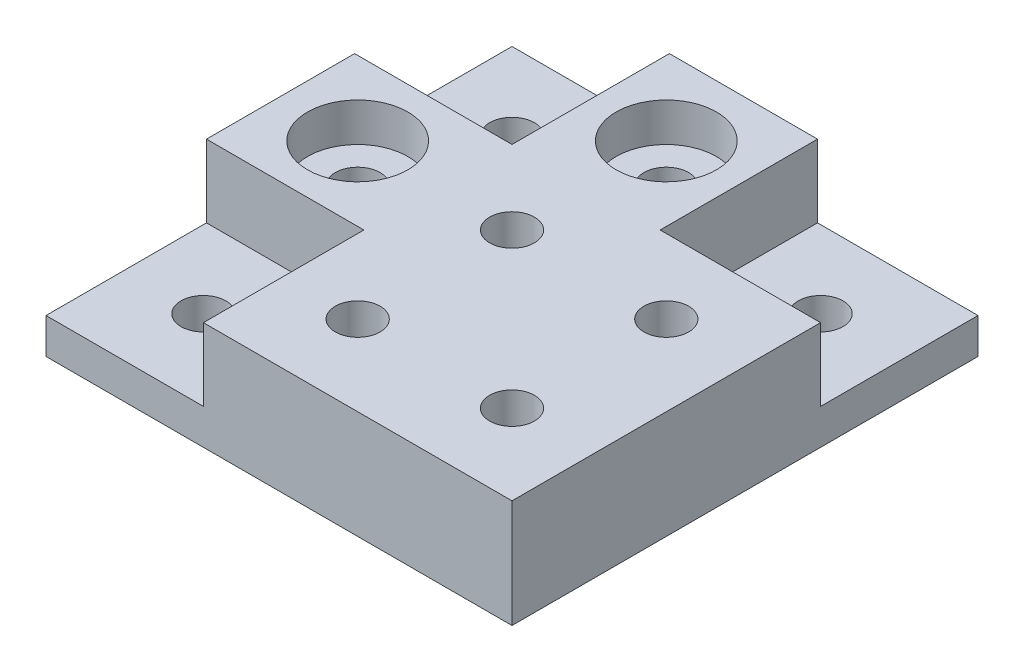
SolidWorks part; units mm, degrees
ref_plane "Alzado" through (0, 0, 0) normal (0, 0, 1) x (1, 0, 0)
ref_plane "Planta" through (0, 0, 0) normal (0, 1, 0) x (1, 0, 0)
ref_plane "Vista lateral" through (0, 0, 0) normal (1, 0, 0) x (0, 0, -1)
sketch "Croquis1" plane through (0, 0, 0) normal (0, 1, 0) x (1, 0, 0)
  line L1 (-50, -50) -> (50, -50)
  line L2 (-50, -50) -> (-50, 50)
  line L3 (-50, 50) -> (50, 50)
  line L4 (50, -50) -> (50, 50)
  line L5 (-50, -50) -> (50, 50) construction
  line L6 (-50, 50) -> (50, -50) construction
  point P0 (0, 0)
  dimension "D1" = 100
  dimension "D2" = 100
extrude "Saliente-Extruir1" add sketch "Croquis1" along normal blind 7
sketch "Croquis2" plane through (0, 7, 0) normal (0, 1, 0) x (1, 0, 0)
  line L45 (-50, 50) -> (-50, -50) construction
  line L50 (-50.2, 50.2) -> (-39.8, 50.2)
  line L55 (-50.2, 50.2) -> (-50.2, 39.8)
  line L60 (-50.2, 39.8) -> (-39.8, 39.8)
  line L65 (-39.8, 50.2) -> (-39.8, 39.8)
  line L70 (50, 50) -> (-50, 50) construction
  line L75 (-30.2, 50.2) -> (-19.8, 50.2)
  line L80 (-30.2, 50.2) -> (-30.2, 39.8)
  line L85 (-30.2, 39.8) -> (-19.8, 39.8)
  line L95 (-19.8, 50.2) -> (-19.8, 39.8)
  line L96 (-10.2, 50.2) -> (0.2, 50.2)
  line L97 (-10.2, 50.2) -> (-10.2, 39.8)
  line L98 (-10.2, 39.8) -> (0.2, 39.8)
  line L99 (0.2, 50.2) -> (0.2, 39.8)
  line L100 (9.8, 50.2) -> (20.2, 50.2)
  line L101 (9.8, 50.2) -> (9.8, 39.8)
  line L102 (9.8, 39.8) -> (20.2, 39.8)
  line L103 (20.2, 50.2) -> (20.2, 39.8)
  line L104 (29.8, 50.2) -> (40.2, 50.2)
  line L105 (29.8, 50.2) -> (29.8, 39.8)
  line L106 (29.8, 39.8) -> (40.2, 39.8)
  line L107 (40.2, 50.2) -> (40.2, 39.8)
  line L108 (-50.2, 30.2) -> (-39.8, 30.2)
  line L109 (-50.2, 30.2) -> (-50.2, 19.8)
  line L110 (-50.2, 19.8) -> (-39.8, 19.8)
  line L111 (-39.8, 30.2) -> (-39.8, 19.8)
  line L112 (-50.2, 10.2) -> (-39.8, 10.2)
  line L113 (-50.2, 10.2) -> (-50.2, -0.2)
  line L114 (-50.2, -0.2) -> (-39.8, -0.2)
  line L115 (-39.8, 10.2) -> (-39.8, -0.2)
  line L116 (-50.2, -9.8) -> (-39.8, -9.8)
  line L117 (-50.2, -9.8) -> (-50.2, -20.2)
  line L118 (-50.2, -20.2) -> (-39.8, -20.2)
  line L119 (-39.8, -9.8) -> (-39.8, -20.2)
  line L120 (-50.2, -29.8) -> (-39.8, -29.8)
  line L121 (-50.2, -29.8) -> (-50.2, -40.2)
  line L122 (-50.2, -40.2) -> (-39.8, -40.2)
  line L123 (-39.8, -29.8) -> (-39.8, -40.2)
  dimension "D3" = 0.2
  dimension "D1" = 10.4
  dimension "D2" = 10.4
  dimension "D4" = 0.2
  dimension "D5" = 5
extrude "Cortar-Extruir1" cut sketch "Croquis2" against normal blind 4.7
sketch "Croquis3" plane through (0, 7, 0) normal (0, 1, 0) x (1, 0, 0)
  line L0 (50, 30) -> (60, 30)
  line L5 (50, 50) -> (60, 50)
  line L6 (50, 50) -> (50, 40)
  line L7 (50, 40) -> (60, 40)
  line L8 (60, 50) -> (60, 40)
  line L9 (50, 30) -> (50, 20)
  line L10 (50, 20) -> (60, 20)
  line L11 (60, 30) -> (60, 20)
  line L12 (50, 10) -> (60, 10)
  line L13 (50, 10) -> (50, 0)
  line L14 (50, 0) -> (60, 0)
  line L15 (60, 10) -> (60, 0)
  line L16 (50, -10) -> (60, -10)
  line L17 (50, -10) -> (50, -20)
  line L18 (50, -20) -> (60, -20)
  line L19 (60, -10) -> (60, -20)
  line L20 (50, -30) -> (60, -30)
  line L21 (50, -30) -> (50, -40)
  line L22 (50, -40) -> (60, -40)
  line L23 (60, -30) -> (60, -40)
  line L24 (-30, -50) -> (-20, -50)
  line L25 (-50, -50) -> (-40, -50)
  line L26 (-50, -50) -> (-50, -60)
  line L27 (-50, -60) -> (-40, -60)
  line L28 (-40, -50) -> (-40, -60)
  line L29 (-30, -50) -> (-30, -60)
  line L30 (-30, -60) -> (-20, -60)
  line L31 (-20, -50) -> (-20, -60)
  line L32 (-10, -50) -> (0, -50)
  line L33 (-10, -50) -> (-10, -60)
  line L34 (-10, -60) -> (0, -60)
  line L35 (0, -50) -> (0, -60)
  line L36 (10, -50) -> (20, -50)
  line L37 (10, -50) -> (10, -60)
  line L38 (10, -60) -> (20, -60)
  line L39 (20, -50) -> (20, -60)
  line L40 (30, -50) -> (40, -50)
  line L41 (30, -50) -> (30, -60)
  line L42 (30, -60) -> (40, -60)
  line L43 (40, -50) -> (40, -60)
  dimension "D1" = 10
  dimension "D2" = 10
  dimension "D4" = 10
  dimension "D5" = 10
  dimension "D3" = 5
extrude "Saliente-Extruir2" add sketch "Croquis3" against normal blind 4.5
sketch "Croquis4" plane through (0, 7, 0) normal (0, 1, 0) x (1, 0, 0)
  line L0 (60, 45) -> (-63.1643, 45) construction
  line L1 (60, 40) -> (60, 50) construction
  line L2 (-45, -60) -> (-45, 61.9533) construction
  line L3 (-50, -60) -> (-40, -60) construction
  circle A0 centre (-45, 45) radius 1.45
  circle A1 centre (-35, 45) radius 1.45
  circle A2 centre (-25, 45) radius 1.45
  circle A3 centre (-15, 45) radius 1.45
  circle A4 centre (-5, 45) radius 1.45
  circle A5 centre (5, 45) radius 1.45
  circle A6 centre (15, 45) radius 1.45
  circle A7 centre (25, 45) radius 1.45
  circle A8 centre (35, 45) radius 1.45
  circle A9 centre (45, 45) radius 1.45
  circle A10 centre (55, 45) radius 1.45
  circle A11 centre (-35, 35) radius 1.45
  circle A12 centre (-25, 35) radius 1.45
  circle A13 centre (-15, 35) radius 1.45
  circle A14 centre (-5, 35) radius 1.45
  circle A15 centre (5, 35) radius 1.45
  circle A16 centre (15, 35) radius 1.45
  circle A17 centre (25, 35) radius 1.45
  circle A18 centre (35, 35) radius 1.45
  circle A19 centre (45, 35) radius 1.45
  circle A20 centre (55, 35) radius 1.45
  circle A21 centre (-35, 25) radius 1.45
  circle A22 centre (-25, 25) radius 1.45
  circle A23 centre (-15, 25) radius 1.45
  circle A24 centre (-5, 25) radius 1.45
  circle A25 centre (5, 25) radius 1.45
  circle A26 centre (15, 25) radius 1.45
  circle A27 centre (25, 25) radius 1.45
  circle A28 centre (35, 25) radius 1.45
  circle A29 centre (45, 25) radius 1.45
  circle A30 centre (55, 25) radius 1.45
  circle A31 centre (-35, 15) radius 1.45
  circle A32 centre (-25, 15) radius 1.45
  circle A33 centre (-15, 15) radius 1.45
  circle A34 centre (-5, 15) radius 1.45
  circle A35 centre (5, 15) radius 1.45
  circle A36 centre (15, 15) radius 1.45
  circle A37 centre (25, 15) radius 1.45
  circle A38 centre (35, 15) radius 1.45
  circle A39 centre (45, 15) radius 1.45
  circle A40 centre (55, 15) radius 1.45
  circle A41 centre (-35, 5) radius 1.45
  circle A42 centre (-25, 5) radius 1.45
  circle A43 centre (-15, 5) radius 1.45
  circle A44 centre (-5, 5) radius 1.45
  circle A45 centre (5, 5) radius 1.45
  circle A46 centre (15, 5) radius 1.45
  circle A47 centre (25, 5) radius 1.45
  circle A48 centre (35, 5) radius 1.45
  circle A49 centre (45, 5) radius 1.45
  circle A50 centre (55, 5) radius 1.45
  circle A51 centre (-35, -5) radius 1.45
  circle A52 centre (-25, -5) radius 1.45
  circle A53 centre (-15, -5) radius 1.45
  circle A54 centre (-5, -5) radius 1.45
  circle A55 centre (5, -5) radius 1.45
  circle A56 centre (15, -5) radius 1.45
  circle A57 centre (25, -5) radius 1.45
  circle A58 centre (35, -5) radius 1.45
  circle A59 centre (45, -5) radius 1.45
  circle A60 centre (55, -5) radius 1.45
  circle A61 centre (-35, -15) radius 1.45
  circle A62 centre (-25, -15) radius 1.45
  circle A63 centre (-15, -15) radius 1.45
  circle A64 centre (-5, -15) radius 1.45
  circle A65 centre (5, -15) radius 1.45
  circle A66 centre (15, -15) radius 1.45
  circle A67 centre (25, -15) radius 1.45
  circle A68 centre (35, -15) radius 1.45
  circle A69 centre (45, -15) radius 1.45
  circle A70 centre (55, -15) radius 1.45
  circle A71 centre (-35, -25) radius 1.45
  circle A72 centre (-25, -25) radius 1.45
  circle A73 centre (-15, -25) radius 1.45
  circle A74 centre (-5, -25) radius 1.45
  circle A75 centre (5, -25) radius 1.45
  circle A76 centre (15, -25) radius 1.45
  circle A77 centre (25, -25) radius 1.45
  circle A78 centre (35, -25) radius 1.45
  circle A79 centre (45, -25) radius 1.45
  circle A80 centre (55, -25) radius 1.45
  circle A81 centre (-35, -35) radius 1.45
  circle A82 centre (-25, -35) radius 1.45
  circle A83 centre (-15, -35) radius 1.45
  circle A84 centre (-5, -35) radius 1.45
  circle A85 centre (5, -35) radius 1.45
  circle A86 centre (15, -35) radius 1.45
  circle A87 centre (25, -35) radius 1.45
  circle A88 centre (35, -35) radius 1.45
  circle A89 centre (45, -35) radius 1.45
  circle A90 centre (55, -35) radius 1.45
  circle A91 centre (-35, -45) radius 1.45
  circle A92 centre (-25, -45) radius 1.45
  circle A93 centre (-15, -45) radius 1.45
  circle A94 centre (-5, -45) radius 1.45
  circle A95 centre (5, -45) radius 1.45
  circle A96 centre (15, -45) radius 1.45
  circle A97 centre (25, -45) radius 1.45
  circle A98 centre (35, -45) radius 1.45
  circle A99 centre (45, -45) radius 1.45
  circle A100 centre (55, -45) radius 1.45
  circle A101 centre (-35, -55) radius 1.45
  circle A102 centre (-25, -55) radius 1.45
  circle A103 centre (-15, -55) radius 1.45
  circle A104 centre (-5, -55) radius 1.45
  circle A105 centre (5, -55) radius 1.45
  circle A106 centre (15, -55) radius 1.45
  circle A107 centre (25, -55) radius 1.45
  circle A108 centre (35, -55) radius 1.45
  circle A109 centre (45, -55) radius 1.45
  circle A110 centre (55, -55) radius 1.45
  circle A111 centre (-45, 35) radius 1.45
  circle A112 centre (-45, 25) radius 1.45
  circle A113 centre (-45, 15) radius 1.45
  circle A114 centre (-45, 5) radius 1.45
  circle A115 centre (-45, -5) radius 1.45
  circle A116 centre (-45, -15) radius 1.45
  circle A117 centre (-45, -25) radius 1.45
  circle A118 centre (-45, -35) radius 1.45
  circle A119 centre (-45, -45) radius 1.45
  circle A120 centre (-45, -55) radius 1.45
  dimension "D1" = 2.9
  dimension "D2" = 11
extrude "Cortar-Extruir2" cut sketch "Croquis4" against normal blind 7
sketch "Croquis5" plane through (0, 7, 0) normal (0, 1, 0) x (1, 0, 0)
  circle A0 centre (-45, 45) radius 3.25
  circle A1 centre (-35, 45) radius 3.25
  circle A2 centre (-25, 45) radius 3.25
  circle A3 centre (-15, 45) radius 3.25
  circle A4 centre (-5, 45) radius 3.25
  circle A5 centre (5, 45) radius 3.25
  circle A6 centre (15, 45) radius 3.25
  circle A7 centre (25, 45) radius 3.25
  circle A8 centre (35, 45) radius 3.25
  circle A9 centre (45, 45) radius 3.25
  circle A10 centre (55, 45) radius 3.25
  circle A20 centre (55, 35) radius 3.25
  circle A30 centre (55, 25) radius 3.25
  circle A40 centre (55, 15) radius 3.25
  circle A50 centre (55, 5) radius 3.25
  circle A60 centre (55, -5) radius 3.25
  circle A70 centre (55, -15) radius 3.25
  circle A80 centre (55, -25) radius 3.25
  circle A90 centre (55, -35) radius 3.25
  circle A100 centre (55, -45) radius 3.25
  circle A101 centre (-35, -55) radius 3.25
  circle A102 centre (-25, -55) radius 3.25
  circle A103 centre (-15, -55) radius 3.25
  circle A104 centre (-5, -55) radius 3.25
  circle A105 centre (5, -55) radius 3.25
  circle A106 centre (15, -55) radius 3.25
  circle A107 centre (25, -55) radius 3.25
  circle A108 centre (35, -55) radius 3.25
  circle A109 centre (45, -55) radius 3.25
  circle A110 centre (55, -55) radius 3.25
  circle A111 centre (-45, 35) radius 3.25
  circle A112 centre (-45, 25) radius 3.25
  circle A113 centre (-45, 15) radius 3.25
  circle A114 centre (-45, 5) radius 3.25
  circle A115 centre (-45, -5) radius 3.25
  circle A116 centre (-45, -15) radius 3.25
  circle A117 centre (-45, -25) radius 3.25
  circle A118 centre (-45, -35) radius 3.25
  circle A119 centre (-45, -45) radius 3.25
  circle A120 centre (-45, -55) radius 3.25
  circle A121 centre (-35, 35) radius 3.25 [skipped]
  circle A122 centre (-25, 35) radius 3.25 [skipped]
  circle A123 centre (-15, 35) radius 3.25 [skipped]
  circle A124 centre (-5, 35) radius 3.25 [skipped]
  circle A125 centre (5, 35) radius 3.25 [skipped]
  circle A126 centre (15, 35) radius 3.25 [skipped]
  circle A127 centre (25, 35) radius 3.25 [skipped]
  circle A128 centre (35, 35) radius 3.25 [skipped]
  circle A129 centre (45, 35) radius 3.25 [skipped]
  circle A130 centre (-35, 25) radius 3.25 [skipped]
  circle A131 centre (-25, 25) radius 3.25 [skipped]
  circle A132 centre (-15, 25) radius 3.25 [skipped]
  circle A133 centre (-5, 25) radius 3.25 [skipped]
  circle A134 centre (5, 25) radius 3.25 [skipped]
  circle A135 centre (15, 25) radius 3.25 [skipped]
  circle A136 centre (25, 25) radius 3.25 [skipped]
  circle A137 centre (35, 25) radius 3.25 [skipped]
  circle A138 centre (45, 25) radius 3.25 [skipped]
  circle A139 centre (-35, 15) radius 3.25 [skipped]
  circle A140 centre (-25, 15) radius 3.25 [skipped]
  circle A141 centre (-15, 15) radius 3.25 [skipped]
  circle A142 centre (-5, 15) radius 3.25 [skipped]
  circle A143 centre (5, 15) radius 3.25 [skipped]
  circle A144 centre (15, 15) radius 3.25 [skipped]
  circle A145 centre (25, 15) radius 3.25 [skipped]
  circle A146 centre (35, 15) radius 3.25 [skipped]
  circle A147 centre (45, 15) radius 3.25 [skipped]
  circle A148 centre (-35, 5) radius 3.25 [skipped]
  circle A149 centre (-25, 5) radius 3.25 [skipped]
  circle A150 centre (-15, 5) radius 3.25 [skipped]
  circle A151 centre (-5, 5) radius 3.25 [skipped]
  circle A152 centre (5, 5) radius 3.25 [skipped]
  circle A153 centre (15, 5) radius 3.25 [skipped]
  circle A154 centre (25, 5) radius 3.25 [skipped]
  circle A155 centre (35, 5) radius 3.25 [skipped]
  circle A156 centre (45, 5) radius 3.25 [skipped]
  circle A157 centre (-35, -5) radius 3.25 [skipped]
  circle A158 centre (-25, -5) radius 3.25 [skipped]
  circle A159 centre (-15, -5) radius 3.25 [skipped]
  circle A160 centre (-5, -5) radius 3.25 [skipped]
  circle A161 centre (5, -5) radius 3.25 [skipped]
  circle A162 centre (15, -5) radius 3.25 [skipped]
  circle A163 centre (25, -5) radius 3.25 [skipped]
  circle A164 centre (35, -5) radius 3.25 [skipped]
  circle A165 centre (45, -5) radius 3.25 [skipped]
  circle A166 centre (-35, -15) radius 3.25 [skipped]
  circle A167 centre (-25, -15) radius 3.25 [skipped]
  circle A168 centre (-15, -15) radius 3.25 [skipped]
  circle A169 centre (-5, -15) radius 3.25 [skipped]
  circle A170 centre (5, -15) radius 3.25 [skipped]
  circle A171 centre (15, -15) radius 3.25 [skipped]
  circle A172 centre (25, -15) radius 3.25 [skipped]
  circle A173 centre (35, -15) radius 3.25 [skipped]
  circle A174 centre (45, -15) radius 3.25 [skipped]
  circle A175 centre (-35, -25) radius 3.25 [skipped]
  circle A176 centre (-25, -25) radius 3.25 [skipped]
  circle A177 centre (-15, -25) radius 3.25 [skipped]
  circle A178 centre (-5, -25) radius 3.25 [skipped]
  circle A179 centre (5, -25) radius 3.25 [skipped]
  circle A180 centre (15, -25) radius 3.25 [skipped]
  circle A181 centre (25, -25) radius 3.25 [skipped]
  circle A182 centre (35, -25) radius 3.25 [skipped]
  circle A183 centre (45, -25) radius 3.25 [skipped]
  circle A184 centre (-35, -35) radius 3.25 [skipped]
  circle A185 centre (-25, -35) radius 3.25 [skipped]
  circle A186 centre (-15, -35) radius 3.25 [skipped]
  circle A187 centre (-5, -35) radius 3.25 [skipped]
  circle A188 centre (5, -35) radius 3.25 [skipped]
  circle A189 centre (15, -35) radius 3.25 [skipped]
  circle A190 centre (25, -35) radius 3.25 [skipped]
  circle A191 centre (35, -35) radius 3.25 [skipped]
  circle A192 centre (45, -35) radius 3.25 [skipped]
  circle A193 centre (-35, -45) radius 3.25 [skipped]
  circle A194 centre (-25, -45) radius 3.25 [skipped]
  circle A195 centre (-15, -45) radius 3.25 [skipped]
  circle A196 centre (-5, -45) radius 3.25 [skipped]
  circle A197 centre (5, -45) radius 3.25 [skipped]
  circle A198 centre (15, -45) radius 3.25 [skipped]
  circle A199 centre (25, -45) radius 3.25 [skipped]
  circle A200 centre (35, -45) radius 3.25 [skipped]
  circle A201 centre (45, -45) radius 3.25 [skipped]
  dimension "D1" = 6.5
  dimension "D3" = 11
  dimension "D2" = 11
extrude "Cortar-Extruir4" cut sketch "Croquis5" against normal blind 2.5
sketch "Croquis6" plane through (0, 7, 0) normal (0, 1, 0) x (1, 0, 0)
  line L0 (50, -50) -> (40, -50)
  line L1 (50, -50) -> (50, -49.8)
  line L2 (40, -50) -> (40, -49.8)
  line L3 (49.8, -49.8) -> (40, -49.8)
  line L4 (30, -50) -> (20, -50)
  line L5 (30, -50) -> (30, -49.8)
  line L6 (20, -50) -> (20, -49.8)
  line L7 (30, -49.8) -> (20, -49.8)
  line L8 (10, -50) -> (0, -50)
  line L9 (10, -50) -> (10, -49.8)
  line L10 (0, -50) -> (0, -49.8)
  line L11 (10, -49.8) -> (0, -49.8)
  line L12 (-10, -50) -> (-20, -50)
  line L13 (-10, -50) -> (-10, -49.8)
  line L14 (-20, -50) -> (-20, -49.8)
  line L15 (-10, -49.8) -> (-20, -49.8)
  line L16 (-30, -50) -> (-40, -50)
  line L17 (-30, -50) -> (-30, -49.8)
  line L18 (-40, -50) -> (-40, -49.8)
  line L19 (-30, -49.8) -> (-40, -49.8)
  line L20 (50, -49.8) -> (50, -40)
  line L22 (50, -40) -> (49.8, -40)
  line L23 (49.8, -49.8) -> (49.8, -40)
  line L24 (50, -29.8) -> (50, -20)
  line L25 (50, -29.8) -> (49.8, -29.8)
  line L26 (50, -20) -> (49.8, -20)
  line L27 (49.8, -29.8) -> (49.8, -20)
  line L28 (50, -9.8) -> (50, 0)
  line L29 (50, -9.8) -> (49.8, -9.8)
  line L30 (50, 0) -> (49.8, 0)
  line L31 (49.8, -9.8) -> (49.8, 0)
  line L32 (50, 10.2) -> (50, 20)
  line L33 (50, 10.2) -> (49.8, 10.2)
  line L34 (50, 20) -> (49.8, 20)
  line L35 (49.8, 10.2) -> (49.8, 20)
  line L36 (50, 30.2) -> (50, 40)
  line L37 (50, 30.2) -> (49.8, 30.2)
  line L38 (50, 40) -> (49.8, 40)
  line L39 (49.8, 30.2) -> (49.8, 40)
  dimension "D1" = 0.2
  dimension "D2" = 0.2
  dimension "D3" = 5
extrude "Cortar-Extruir5" cut sketch "Croquis6" against normal blind 7
sketch "Croquis8" plane through (0, 7, 0) normal (0, 1, 0) x (1, 0, 0)
  line L1 (49.8, 40) -> (60, 40)
  line L2 (49.8, 40) -> (49.8, 50)
  line L3 (49.8, 50) -> (60, 50)
  line L4 (60, 40) -> (60, 50)
extrude "Cortar-Extruir7" cut sketch "Croquis8" against normal blind 7
sketch "Croquis9" plane through (0, 0, 0) normal (0, -1, 0) x (1, 0, 0)
  line L0 (-40, 50) -> (-40, 49.8)
  line L1 (-40, 50) -> (-50.0122, 50)
  line L2 (-40, 49.8) -> (-50.0122, 49.8)
  line L3 (-50.0122, 50) -> (-50.0122, 49.8)
  line L4 (-20, 50) -> (-20, 49.8)
  line L5 (-20, 50) -> (-30.0122, 50)
  line L6 (-20, 49.8) -> (-30.0122, 49.8)
  line L7 (-30.0122, 50) -> (-30.0122, 49.8)
  line L8 (0, 50) -> (0, 49.8)
  line L9 (0, 50) -> (-10.0122, 50)
  line L10 (0, 49.8) -> (-10.0122, 49.8)
  line L11 (-10.0122, 50) -> (-10.0122, 49.8)
  line L12 (20, 50) -> (20, 49.8)
  line L13 (20, 50) -> (9.9878, 50)
  line L14 (20, 49.8) -> (9.9878, 49.8)
  line L15 (9.9878, 50) -> (9.9878, 49.8)
  line L16 (40, 50) -> (40, 49.8)
  line L17 (40, 50) -> (29.9878, 50)
  line L18 (40, 49.8) -> (29.9878, 49.8)
  line L19 (29.9878, 50) -> (29.9878, 49.8)
  line L20 (50, -20) -> (50, -30.2)
  line L21 (50, -20) -> (49.8, -20)
  line L22 (50, -30.2) -> (49.8, -30.2)
  line L23 (49.8, -20) -> (49.8, -30.2)
  line L24 (49.8, -50) -> (49.8, -30.2) construction
  line L25 (50, 0) -> (50, -10.2)
  line L26 (50, 0) -> (49.8, 0)
  line L27 (50, -10.2) -> (49.8, -10.2)
  line L28 (49.8, 0) -> (49.8, -10.2)
  line L29 (50, 20) -> (50, 9.8)
  line L30 (50, 20) -> (49.8, 20)
  line L31 (50, 9.8) -> (49.8, 9.8)
  line L32 (49.8, 20) -> (49.8, 9.8)
  line L33 (50, 40) -> (50, 29.8)
  line L34 (50, 40) -> (49.8, 40)
  line L35 (50, 29.8) -> (49.8, 29.8)
  line L36 (49.8, 40) -> (49.8, 29.8)
  dimension "D1" = 0
  dimension "D2" = 4
extrude "Cortar-Extruir9" cut sketch "Croquis9" against normal blind 2.5
sketch "Croquis10" plane through (0, 2.5, 0) normal (0, -1, 0) x (1, 0, 0)
  line L0 (50, 30) -> (50, 29.8)
  line L1 (50, 30) -> (49.8, 30)
  line L2 (50, 29.8) -> (49.8, 29.8)
  line L3 (49.8, 30) -> (49.8, 29.8)
  line L4 (50, 10) -> (50, 9.8)
  line L5 (50, 10) -> (49.8, 10)
  line L6 (49.8, 10) -> (49.8, 9.8)
  line L7 (50, 9.8) -> (49.8, 9.8)
  line L8 (50, -10) -> (50, -10.2)
  line L9 (50, -10) -> (49.8, -10)
  line L10 (49.8, -10) -> (49.8, -10.2)
  line L11 (50, -10.2) -> (49.8, -10.2)
  line L12 (50, -30) -> (50, -30.2)
  line L13 (50, -30) -> (49.8, -30)
  line L14 (49.8, -30) -> (49.8, -30.2)
  line L15 (50, -30.2) -> (49.8, -30.2)
  line L16 (49.8, -20) -> (49.8, -30.2) construction
  dimension "D2" = 0
  dimension "D1" = 4
extrude "Cortar-Extruir11" cut sketch "Croquis10" against normal blind 5
sketch "Croquis11" plane through (0, 7, 0) normal (0, 1, 0) x (1, 0, 0)
  line L1 (-50, 19.8) -> (-19.8, 19.8)
  line L2 (-50, 19.8) -> (-50, -65.4733)
  line L3 (-50, -65.4733) -> (71.6522, -65.4733)
  line L4 (71.6522, 19.8) -> (71.6522, -65.4733)
  line L5 (-19.8, 50) -> (71.6522, 50)
  line L6 (-19.8, 50) -> (-19.8, 19.8)
  line L8 (71.6522, 50) -> (71.6522, 19.8)
extrude "Cortar-Extruir14" cut sketch "Croquis11" against normal blind 15
